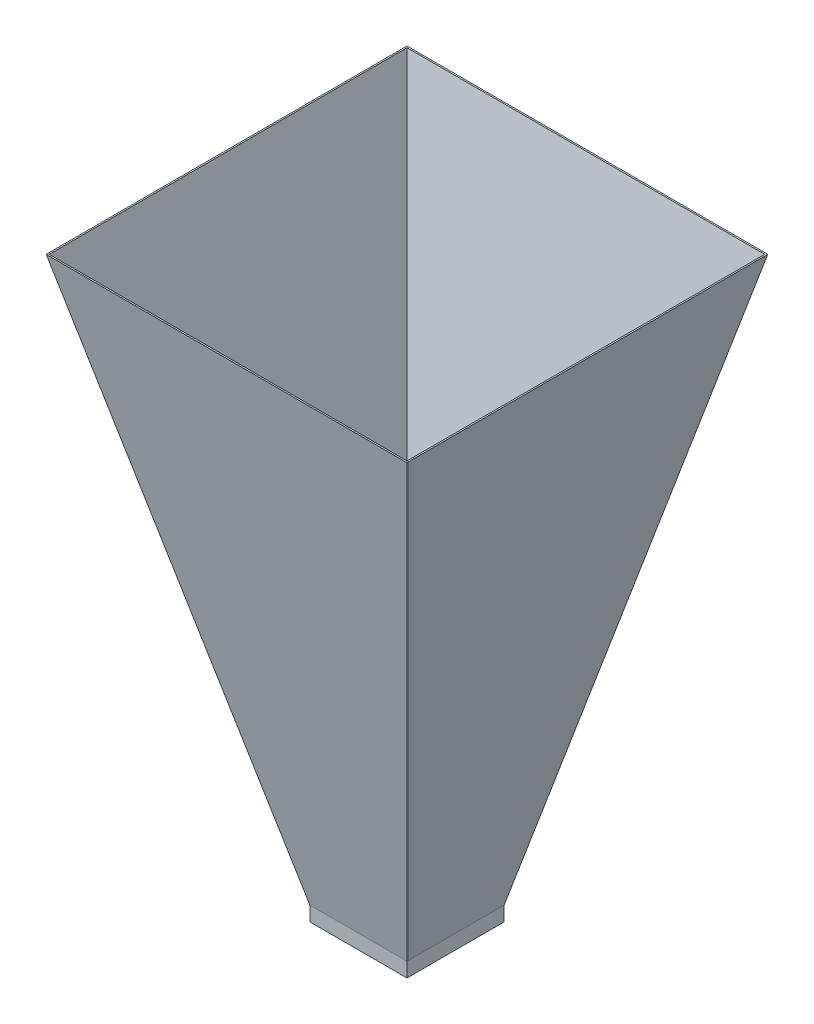
SolidWorks part; units mm, degrees
other "base"
ref_plane "Front Plane" through (0, 0, 0) normal (0, 0, 1) x (1, 0, 0)
ref_plane "Top Plane" through (0, 0, 0) normal (0, 1, 0) x (1, 0, 0)
ref_plane "Right Plane" through (0, 0, 0) normal (1, 0, 0) x (0, 0, -1)
sketch "Sketch2" plane through (0, 0, 0) normal (1, 0, 0) x (0, 0, -1)
  line L0 (0, 20) -> (0, 409) construction
  dimension "D1" = 389
  dimension "D2" = 20
ref_plane "Plane2" through (0, 20, 0) normal (0, 1, 0) x (1, 0, 0)
sketch "Sketch1" plane through (0, 20, 0) normal (0, 1, 0) x (1, 0, 0)
  line L1 (-33.5, -33.5) -> (33.5, -33.5)
  line L2 (-33.5, -33.5) -> (-33.5, 33.5)
  line L3 (-33.5, 33.5) -> (33.5, 33.5)
  line L4 (33.5, -33.5) -> (33.5, 33.5)
  line L5 (-33.5, -33.5) -> (33.5, 33.5) construction
  line L6 (-33.5, 33.5) -> (33.5, -33.5) construction
  point P0 (0, 0)
  dimension "D2" = 67
ref_plane "Plane1" through (0, 409, 0) normal (0, 1, 0) x (1, 0, 0)
sketch "Sketch3" plane through (0, 409, 0) normal (0, 1, 0) x (1, 0, 0)
  line L0 (-124.5, 124.5) -> (-124.5, -124.5)
  line L1 (-124.5, -124.5) -> (124.5, -124.5)
  line L2 (124.5, -124.5) -> (124.5, 124.5)
  line L3 (124.5, 124.5) -> (-124.5, 124.5)
  point P4 (0, 124.5)
  point P5 (124.5, 0)
  dimension "300" = 249
loft "Loft1" add profiles "Sketch1", "Sketch3"
sketch "Sketch4" plane through (0, 20, 0) normal (0, -1, 0) x (1, 0, 0)
  line L4 (33.5, -33.5) -> (33.5, 33.5)
  line L5 (33.5, 33.5) -> (-33.5, 33.5)
  line L6 (-33.5, 33.5) -> (-33.5, -33.5)
  line L7 (-33.5, -33.5) -> (33.5, -33.5)
  line L8 (33.5, -33.5) -> (33.5, 33.5)
  line L9 (33.5, 33.5) -> (-33.5, 33.5)
  line L10 (-33.5, 33.5) -> (-33.5, -33.5)
  line L11 (-33.5, -33.5) -> (33.5, -33.5)
  dimension "D1" = 0
extrude "Boss-Extrude1" add sketch "Sketch4" along normal blind 10
shell "Shell1" thickness 1
split "Split2" trim tools "Plane2" bodies to split 102 resulting bodies 107 108
sketch "Sketch5" plane through (0, -6.1647, 26.3522) normal (0, 0.2278, -0.9737) x (-1, 0, 0)
  line L1 (-279.2532, 629.6458) -> (354.1717, 629.6458)
  line L2 (-279.2532, 629.6458) -> (-279.2532, -419.2924)
  line L3 (-279.2532, -419.2924) -> (354.1717, -419.2924)
  line L4 (354.1717, 629.6458) -> (354.1717, -419.2924)
surface "Surface-Plane1" sketch "Sketch5"
sketch "Sketch6" plane through (-26.3522, -6.1647, 0) normal (0.9737, 0.2278, 0) x (0, 0, -1)
  line L1 (-267.9277, 543.537) -> (347.6129, 543.537)
  line L2 (-267.9277, 543.537) -> (-267.9277, -131.5636)
  line L3 (-267.9277, -131.5636) -> (347.6129, -131.5636)
  line L4 (347.6129, 543.537) -> (347.6129, -131.5636)
surface "Surface-Plane2" sketch "Sketch6"
split "Split1" trimming surface bodies 103 bodies to split 108 102 resulting bodies 105 106
